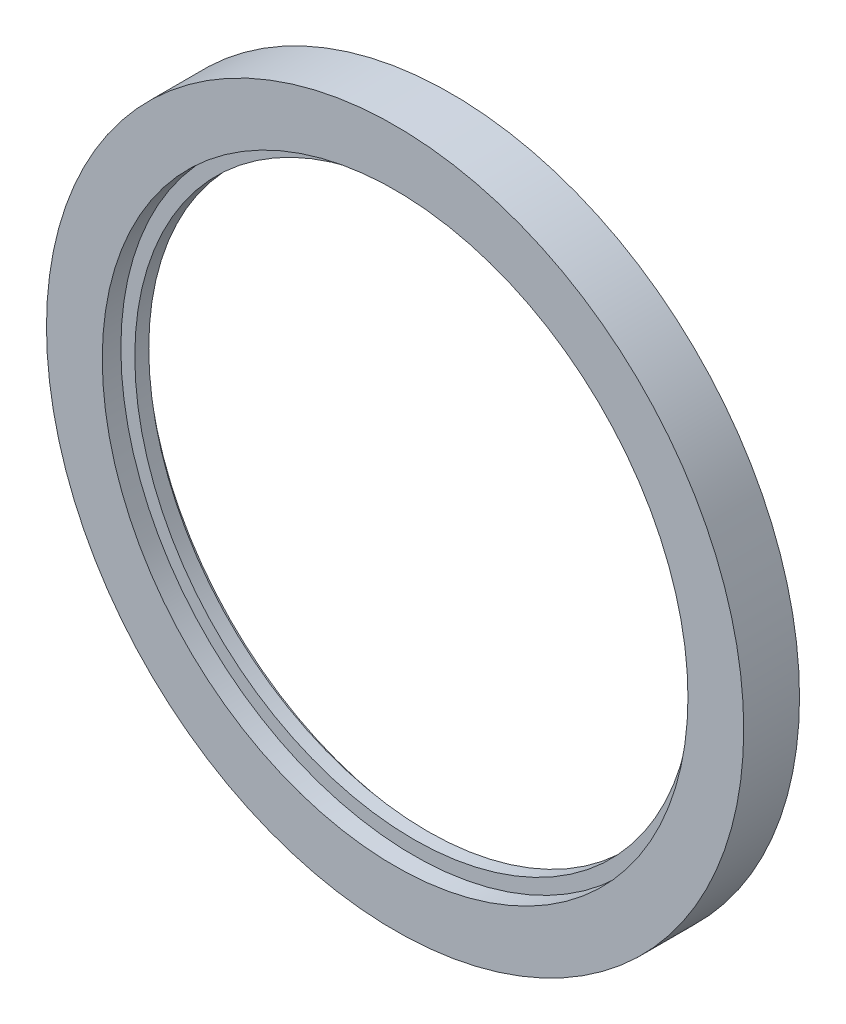
SolidWorks part; units mm, degrees
material "橡胶"
ref_plane "前视基准面" through (0, 0, 0) normal (0, 0, 1) x (1, 0, 0)
ref_plane "上视基准面" through (0, 0, 0) normal (0, 1, 0) x (1, 0, 0)
ref_plane "右视基准面" through (0, 0, 0) normal (1, 0, 0) x (0, 0, -1)
other "Configuration Table"
sketch "草图1" plane through (0, 0, 0) normal (0, 0, 1) x (1, 0, 0)
  circle A0 centre (0, 0) radius 75
  circle A1 centre (0, 0) radius 67.5
extrude "01_CASE_D135" add sketch "草图1" along normal blind 3.3
ref_plane "Pl_1" through (0, 0, 3.3) normal (0, 0, 1) x (1, 0, 0)
sketch "草图2" plane through (0, 0, 3.3) normal (0, 0, 1) x (1, 0, 0)
  circle A0 centre (0, 0) radius 75
  circle A1 centre (0, 0) radius 62
extrude "02_LIP_CONE" add sketch "草图2" along normal blind 1.7
ref_plane "Pl_2" through (0, 0, 5) normal (0, 0, 1) x (1, 0, 0)
sketch "草图3" plane through (0, 0, 5) normal (0, 0, 1) x (1, 0, 0)
  circle A0 centre (0, 0) radius 75
  circle A1 centre (0, 0) radius 60
extrude "03_LIP_D120" add sketch "草图3" along normal blind 3
ref_plane "Pl_3" through (0, 0, 8) normal (0, 0, 1) x (1, 0, 0)
sketch "草图4" plane through (0, 0, 8) normal (0, 0, 1) x (1, 0, 0)
  circle A0 centre (0, 0) radius 75
  circle A1 centre (0, 0) radius 63
extrude "04_DUST_LIP" add sketch "草图4" along normal blind 4
